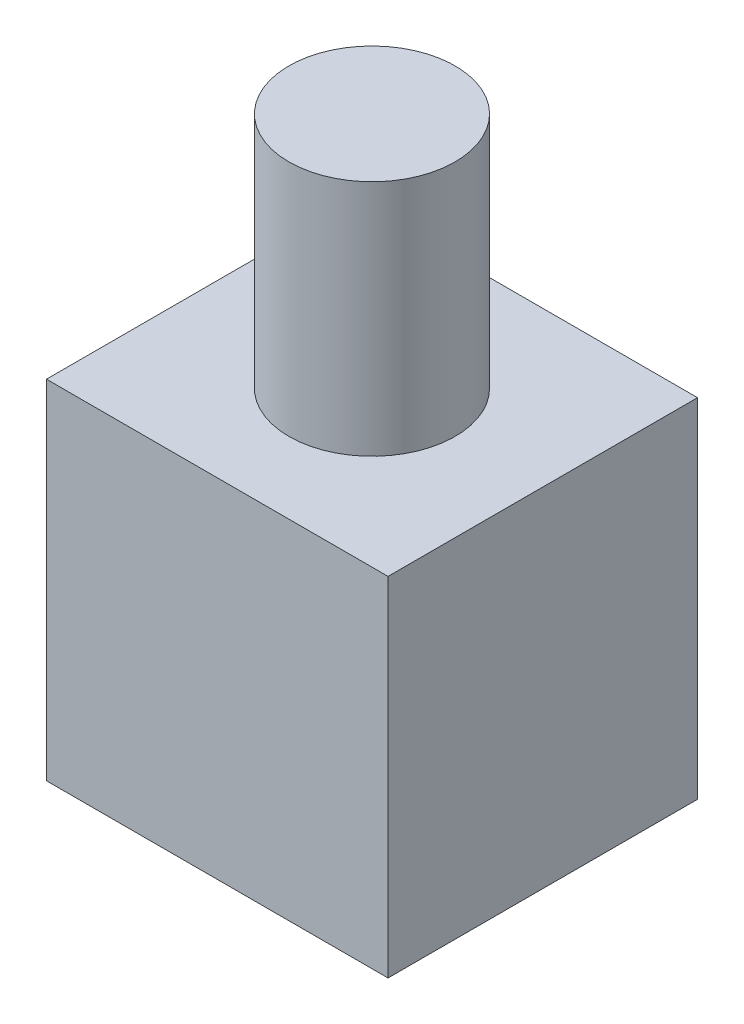
SolidWorks part; units mm, degrees
ref_plane "Front Plane" through (0, 0, 0) normal (0, 0, 1) x (1, 0, 0)
ref_plane "Top Plane" through (0, 0, 0) normal (0, 1, 0) x (1, 0, 0)
ref_plane "Right Plane" through (0, 0, 0) normal (1, 0, 0) x (0, 0, -1)
sketch "Sketch1" plane through (0, 0, 0) normal (0, 1, 0) x (1, 0, 0)
  line L0 (0, 0) -> (12.57, 0)
  line L1 (12.57, 0) -> (12.57, 11.39)
  line L2 (12.57, 11.39) -> (0, 11.39)
  line L3 (0, 11.39) -> (0, 0)
  dimension "D1" = 11.39
  dimension "D2" = 12.57
extrude "Boss-Extrude1" add sketch "Sketch1" along normal blind 12.8
sketch "Sketch2" plane through (0, 12.8, 0) normal (0, 1, 0) x (1, 0, 0)
  line L0 (0, 11.39) -> (12.57, 0) construction
  line L1 (12.57, 11.39) -> (0, 0) construction
  circle A0 centre (6.285, 5.695) radius 3.06
  dimension "D1" = 6.12
extrude "Boss-Extrude2" add sketch "Sketch2" along normal blind 8.75
sketch "Sketch5" plane through (0, 12.8, 0) normal (0, 1, 0) x (1, 0, 0)
  circle A0 centre (6.285, 5.695) radius 3.0262
